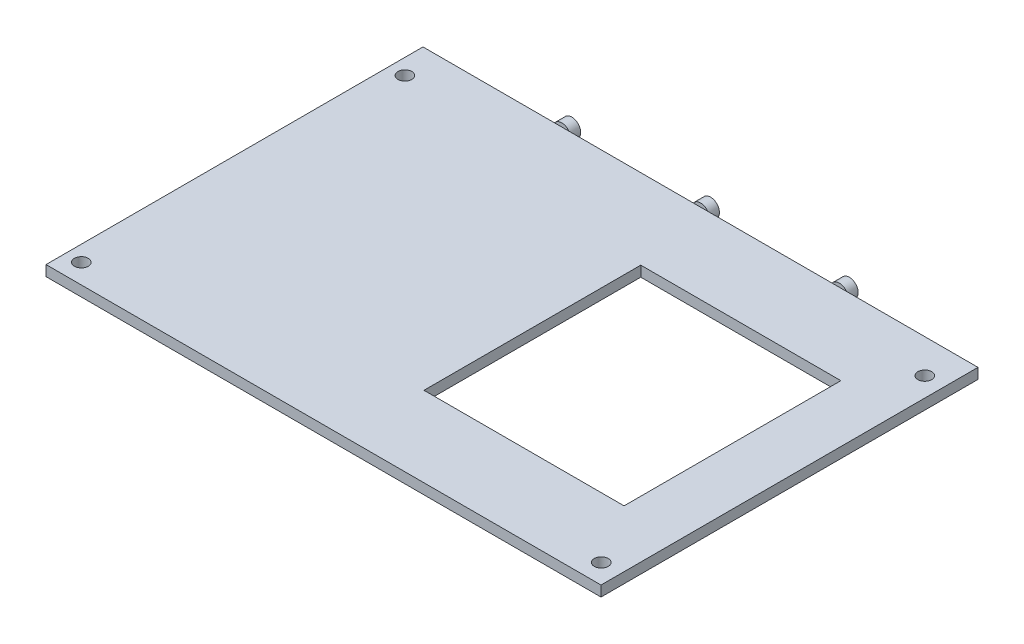
SolidWorks part; units mm, degrees
ref_plane "Front Plane" through (0, 0, 0) normal (0, 0, 1) x (1, 0, 0)
ref_plane "Top Plane" through (0, 0, 0) normal (0, 1, 0) x (1, 0, 0)
ref_plane "Right Plane" through (0, 0, 0) normal (1, 0, 0) x (0, 0, -1)
sketch "Sketch2" plane through (0, 0, 0) normal (0, 0, 1) x (1, 0, 0)
  line L1 (-53, 1) -> (53, 1)
  line L2 (-53, 1) -> (-53, -1)
  line L3 (-53, -1) -> (53, -1)
  line L4 (53, 1) -> (53, -1)
  line L5 (-53, 1) -> (53, -1) construction
  line L6 (-53, -1) -> (53, 1) construction
  point P0 (0, 0)
  dimension "D1" = 106
  dimension "D2" = 2
extrude "Boss-Extrude1" add sketch "Sketch2" along normal blind 72
sketch "Sketch4" plane through (0, 1, 0) normal (0, 1, 0) x (1, 0, 0)
  line L0 (-53, -72) -> (53, -72) construction
  line L1 (53, -72) -> (53, 0) construction
  line L2 (-62.6793, -72) -> (-62.6793, -4) construction
  line L3 (-50.0049, -4) -> (-53, -4) construction
  line L4 (-53, -72) -> (-53, 0) construction
  line L5 (-53, -4) -> (53, -4) construction
  line L6 (-56.8726, -4) -> (-56.8726, -6.4507) construction
  line L7 (-55.3882, -72) -> (-55.3882, -68.2507) construction
  line L8 (53, -77.5021) -> (49.2951, -77.5021) construction
  line L9 (53, 3.1613) -> (49.2951, 3.1613) construction
  line L10 (-53.7098, 3.1613) -> (-50.0049, 3.1613) construction
  line L11 (-53, -36) -> (53, -36) construction
  line L12 (0, 0) -> (0, -72) construction
  line L13 (53, 0) -> (-53, 0) construction
  circle A0 centre (-50.0049, -68.2507) radius 1.325
  circle A1 centre (49.2951, -68.2507) radius 1.325
  circle A2 centre (49.2951, -6.4507) radius 1.325
  circle A3 centre (-50.0049, -6.4507) radius 1.325
  dimension "D6" = 2.65
  dimension "D1" = 106
  dimension "D2" = 72
  dimension "D3" = 68
  dimension "D4" = 99.3
  dimension "D5" = 61.8
extrude "Cut-Extrude1" cut sketch "Sketch4" against normal through all contours A3 | A0 | A1 | A2
sketch "Sketch5" plane through (0, 0, 0) normal (0, 0, -1) x (-1, 0, 0)
  line L0 (-53, 0) -> (53, 0) construction
  line L1 (-53, -1) -> (-53, 1) construction
  line L2 (53, 1) -> (53, -1) construction
  circle A0 centre (0, 0) radius 1.7
  circle A1 centre (26.5, 0) radius 1.7
  circle A2 centre (-26.5, 0) radius 1.7
  dimension "D3" = 3.4
  dimension "D1" = 26.5
  dimension "D2" = 26.5
sketch "Sketch6" plane through (0, 1, 0) normal (0, 1, 0) x (1, 0, 0)
  line L0 (0, 0) -> (0, -72) construction
  line L1 (53, -72) -> (-53, -72) construction
  line L2 (-53, -36) -> (53, -36) construction
  line L3 (-53, -72) -> (-53, 0) construction
  line L4 (53, -72) -> (53, 0) construction
  line L6 (3.8895, -15.2958) -> (42.1105, -15.2958)
  line L7 (3.8895, -15.2958) -> (3.8895, -56.7042)
  line L8 (3.8895, -56.7042) -> (42.1105, -56.7042)
  line L9 (42.1105, -15.2958) -> (42.1105, -56.7042)
  line L10 (3.8895, -15.2958) -> (42.1105, -56.7042) construction
  line L11 (3.8895, -56.7042) -> (42.1105, -15.2958) construction
  point P11 (23, -36)
  dimension "D1" = 23
  dimension "D2" = 30
extrude "Cut-Extrude3" cut sketch "Sketch6" against normal blind 10
extrude "Boss-Extrude2" add sketch "Sketch5" along normal blind 1.92
